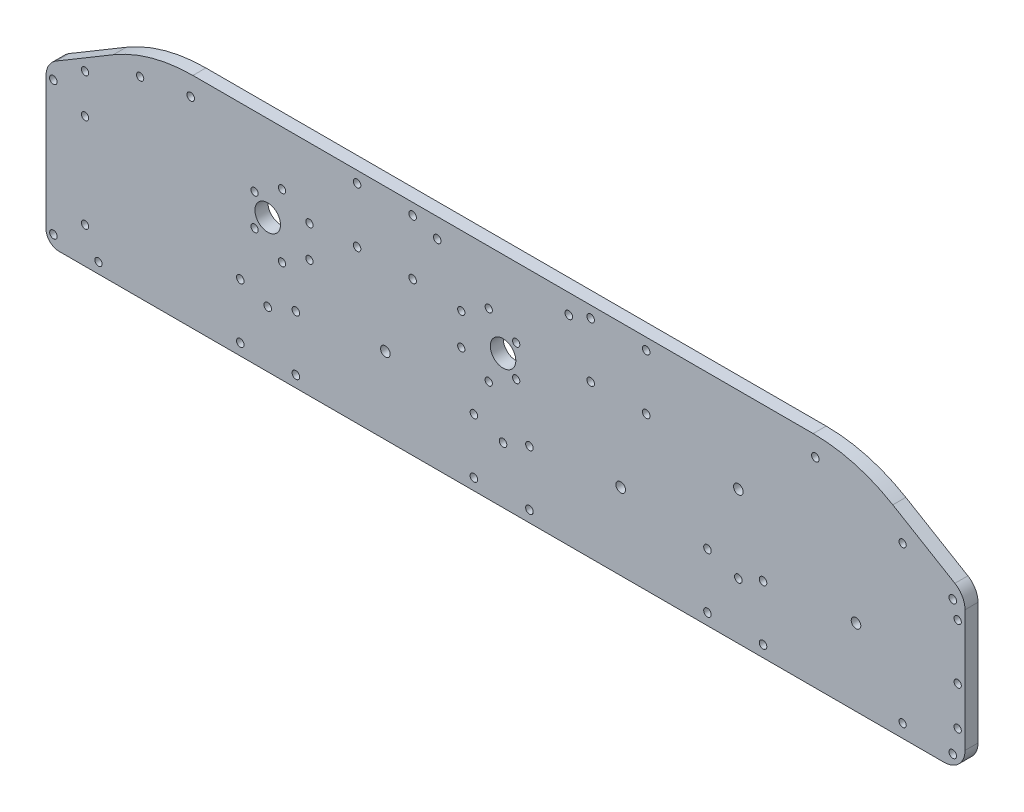
SolidWorks part; units mm, degrees
ref_plane "Front Plane" through (0, 0, 0) normal (0, 0, 1) x (1, 0, 0)
ref_plane "Top Plane" through (0, 0, 0) normal (0, 1, 0) x (1, 0, 0)
ref_plane "Right Plane" through (0, 0, 0) normal (1, 0, 0) x (0, 0, -1)
sketch "Sketch1" plane through (0, 0, 0) normal (0, 0, 1) x (1, 0, 0)
  line L0 (-228.6, 0) -> (228.6, 0) construction
  line L1 (0, -1000) -> (0, 49000) construction
  line L2 (0, 0) -> (0, -6.35)
  line L3 (226.06, 0) -> (226.06, -27.2878)
  line L4 (228.6, 0) -> (226.06, 0) construction
  line L5 (215.9, -37.4478) -> (-215.9, -37.4478)
  line L6 (-223.6374, 33.766) -> (-223.6374, -31.0978)
  line L7 (-115.1471, 27.9528) -> (-108.1471, 27.9528) construction
  line L8 (-151.7577, 69.85) -> (151.7577, 69.85)
  line L9 (-71.418, 37.3296) -> (-71.418, -2.7484)
  line L10 (-71.418, -2.7484) -> (-128.568, -2.7484) construction
  line L11 (-226.06, 0) -> (-226.06, 32.3239)
  line L12 (-190.7328, 59.1281) -> (-218.6741, 42.4964)
  line L13 (-215.9, -37.4478) -> (-217.2874, -37.4478)
  line L16 (190.7328, 59.1281) -> (221.0967, 41.0544)
  line L17 (-0.0009, 27.952) -> (-7.0009, 27.952) construction
  line L20 (-82.9742, 60.325) -> (-152.8242, 60.325) construction
  line L21 (-32.1742, 60.325) -> (-82.9742, 60.325) construction
  line L22 (32.1742, 60.325) -> (82.9742, 60.325) construction
  line L23 (82.9742, 60.325) -> (152.8242, 60.325) construction
  line L34 (226.06, 0) -> (226.06, 32.3239)
  circle A0 centre (-172.72, 0) radius 50.8 construction
  circle A1 centre (172.72, 0) radius 50.8 construction
  circle A2 centre (-57.5742, 0) radius 50.8 construction
  circle A3 centre (57.5725, 0) radius 50.8 construction
  arc A4 (-190.7328, 59.1281) -> (-151.7577, 69.85) centre (-151.7577, -6.35) cw
  circle A5 centre (-57.5742, 0) radius 2.35
  circle A6 centre (57.5725, 0) radius 2.35
  circle A7 centre (172.72, 0) radius 2.35
  circle A8 centre (-172.72, 0) radius 32 construction
  circle A9 centre (-57.5742, 0) radius 32 construction
  circle A10 centre (57.5725, 0) radius 32 construction
  circle A11 centre (172.72, 0) radius 32 construction
  circle A12 centre (-115.1471, 27.9528) radius 32 construction
  circle A13 centre (-0.0009, 27.952) radius 32 construction
  circle A14 centre (115.1462, 27.9511) radius 32 construction
  circle A15 centre (-115.1471, 27.9528) radius 6.25
  circle A16 centre (-0.0009, 27.952) radius 6.25
  circle A17 centre (115.1462, 27.9511) radius 2.35
  arc A18 (204.0836, -6.35) -> (141.3564, -6.35) centre (172.72, 0) cw
  arc A19 (88.9361, -6.35) -> (26.2088, -6.35) centre (57.5725, 0) cw
  arc A20 (151.7577, 69.85) -> (190.7328, 59.1281) centre (151.7577, -6.35) cw
  arc A21 (-218.6741, 42.4964) -> (-223.6374, 33.766) centre (-213.4774, 33.766) ccw
  circle A22 centre (-108.1471, 27.9528) radius 15.5 construction
  circle A23 centre (-108.1471, 43.4528) radius 1.778
  circle A24 centre (-94.7237, 35.7028) radius 1.778
  circle A25 centre (-94.7237, 20.2028) radius 1.778
  circle A26 centre (-108.1471, 12.4528) radius 1.778
  circle A27 centre (-121.5705, 20.2028) radius 1.778
  circle A28 centre (-121.5705, 35.7028) radius 1.778
  circle A29 centre (-7.0009, 27.952) radius 15.5 construction
  circle A30 centre (-7.0009, 43.452) radius 1.778
  circle A31 centre (6.4225, 35.702) radius 1.778
  circle A32 centre (6.4225, 20.202) radius 1.778
  circle A33 centre (-7.0009, 12.452) radius 1.778
  circle A34 centre (-20.4242, 20.202) radius 1.778
  circle A35 centre (-20.4242, 35.702) radius 1.778
  circle A36 centre (-71.418, 64.2704) radius 1.85
  circle A37 centre (-32.1742, 60.325) radius 1.85
  circle A38 centre (-152.8242, 60.325) radius 1.85
  circle A39 centre (152.8242, 60.325) radius 1.85
  circle A40 centre (32.1742, 60.325) radius 1.85
  circle A41 centre (-44.2324, 64.2704) radius 1.85
  circle A42 centre (115.1454, -9.8972) radius 1.85
  circle A43 centre (-115.1471, -9.8972) radius 1.85
  arc A44 (-217.2874, -37.4478) -> (-223.6374, -31.0978) centre (-217.2874, -31.0978) cw
  arc A45 (226.06, -27.2878) -> (215.9, -37.4478) centre (215.9, -27.2878) cw
  circle A46 centre (-0.0013, -9.8972) radius 1.85
  arc A47 (221.0967, 41.0544) -> (226.06, 32.3239) centre (215.9, 32.3239) cw
  circle A48 centre (220.0588, 33.8135) radius 1.85
  circle A49 centre (-220.0588, 33.8135) radius 1.85
  circle A50 centre (220.0588, -31.7528) radius 1.85
  circle A51 centre (-220.0001, -31.651) radius 1.85
  circle A52 centre (-71.418, 37.3296) radius 1.85
  circle A53 centre (-44.2324, 37.3296) radius 1.85
  circle A54 centre (42.882, 64.2704) radius 1.85
  circle A55 centre (70.0676, 64.2704) radius 1.85
  circle A56 centre (42.882, 37.3296) radius 1.85
  circle A57 centre (70.0676, 37.3296) radius 1.85
  circle A58 centre (-128.568, -4.9274) radius 1.85
  circle A59 centre (-101.3824, -4.9274) radius 1.85
  circle A60 centre (-101.3824, -31.8681) radius 1.85
  circle A61 centre (-128.568, -31.8681) radius 1.85
  circle A62 centre (-14.268, -4.9274) radius 1.85
  circle A63 centre (12.9176, -4.9274) radius 1.85
  circle A64 centre (12.9176, -31.8681) radius 1.85
  circle A65 centre (-14.268, -31.8681) radius 1.85
  circle A66 centre (100.032, -4.9274) radius 1.85
  circle A67 centre (127.2176, -4.9274) radius 1.85
  circle A68 centre (127.2176, -31.8681) radius 1.85
  circle A69 centre (100.032, -31.8681) radius 1.85
  circle A70 centre (195.5276, 45.2204) radius 1.778
  circle A71 centre (222.4684, 26.1704) radius 1.778
  circle A72 centre (222.4684, -19.8204) radius 1.778
  circle A73 centre (195.5276, -30.9796) radius 1.778
  circle A74 centre (222.4684, -0.7704) radius 1.778
  circle A75 centre (-177.5816, 56.3796) radius 1.778
  circle A76 centre (-204.5224, 45.2204) radius 1.778
  circle A77 centre (-197.9668, -32.3148) radius 1.778
  circle A78 centre (-204.5224, -19.8204) radius 1.778
  circle A79 centre (-204.5224, 26.1704) radius 1.778
  point P4 (0, 0)
  point P38 (0, -6.35)
  point P41 (-172.72, 69.85)
  point P67 (-108.1471, 27.9528)
  point P69 (172.72, 69.85)
  point P82 (-7.0009, 27.952)
  point P88 (-57.5742, 60.325)
  point P96 (57.5742, 60.325)
  point P97 (-226.06, 38.1)
  point P109 (226.06, 38.1)
  point P134 (56.7258, 60.325)
  dimension "D1" = 101.6
  dimension "D3" = 101.6
  dimension "D5" = 101.6
  dimension "D7" = 101.6
  dimension "D10" = 76.2
  dimension "D11" = 4.7
  dimension "D12" = 4.7
  dimension "D13" = 4.7
  dimension "D14" = 64
  dimension "D15" = 64
  dimension "D16" = 64
  dimension "D17" = 64
  dimension "D20" = 64
  dimension "D21" = 64
  dimension "D24" = 64
  dimension "D26" = 64
  dimension "D27" = 4.7
  dimension "D28" = 12.5
  dimension "D29" = 12.5
  dimension "D30" = 6
  dimension "D31" = 6
  dimension "D32" = 69.85
  dimension "D33" = 76.2
  dimension "D34" = 10.16
  dimension "D35" = 6.35
  dimension "D36" = 10.16
  dimension "D37" = 10.16
  dimension "D38" = 2
  dimension "D39" = 3
  dimension "D2" = 55.88
  dimension "D4" = 55.88
  dimension "D6" = 115.1458
  dimension "D8" = 115.1467
  dimension "D9" = 115.1475
  dimension "D18" = 64
  dimension "D19" = 64
  dimension "D22" = 64
  dimension "D23" = 64
  dimension "D25" = 64
extrude "Boss-Extrude3" add sketch "Sketch1" along normal blind 6.35
